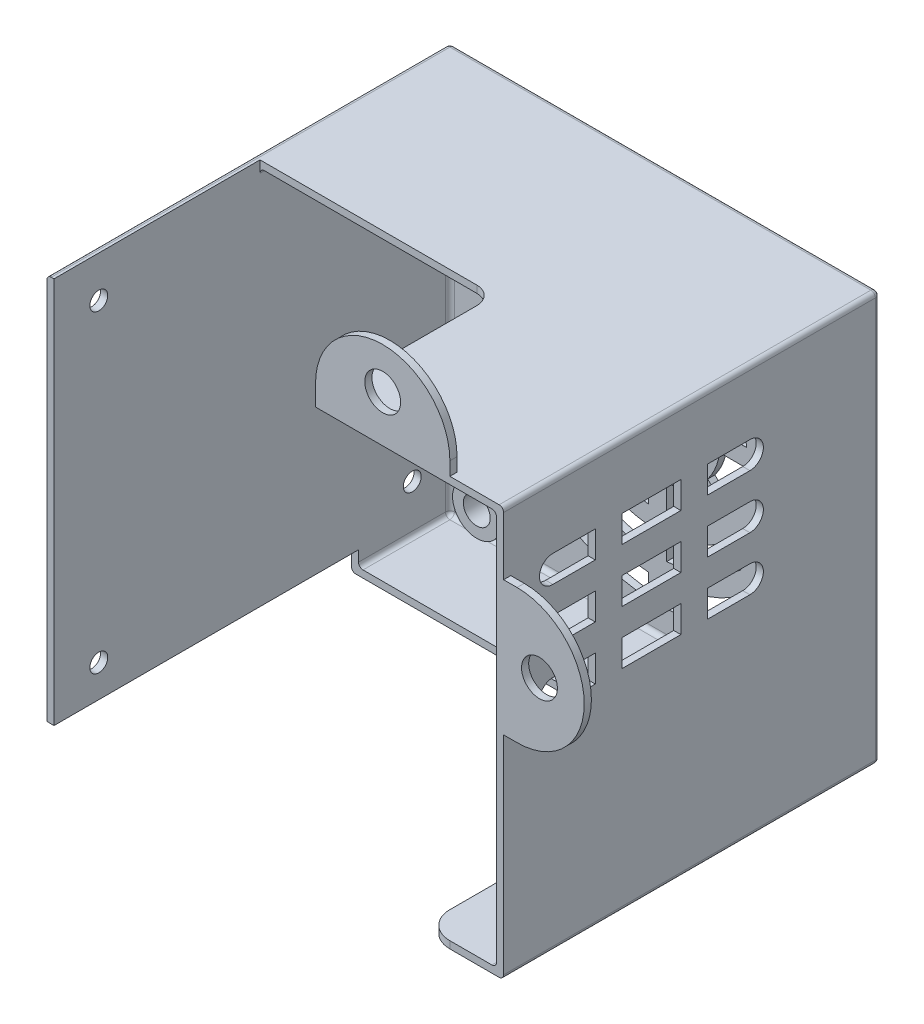
SolidWorks part; units mm, degrees
ref_plane "Front Plane" through (0, 0, 0) normal (0, 0, 1) x (1, 0, 0)
ref_plane "Top Plane" through (0, 0, 0) normal (0, 1, 0) x (1, 0, 0)
ref_plane "Right Plane" through (0, 0, 0) normal (1, 0, 0) x (0, 0, -1)
ref_plane "Plane1" through (0, 0, 42) normal (0, 0, 1) x (1, 0, 0)
sketch "Sketch1" plane through (0, 0, 42) normal (0, 0, 1) x (1, 0, 0)
  line L0 (22.5, 23.6) -> (-25.5, 23.6)
  line L1 (-25.5, 23.6) -> (-25.5, -22.1)
  line L2 (-25.5, -22.1) -> (22.5, -22.1)
  line L3 (22.5, -22.1) -> (22.5, 23.6)
extrude "Boss-Extrude1" add sketch "Sketch1" against normal blind 42
sketch "Sketch2" plane through (0, 23.6, 0) normal (0, 1, 0) x (-1, 0, 0)
  line L0 (25.5, 42) -> (-1.5, 42)
  line L1 (-1.5, 42) -> (-1.5, 22)
  line L2 (-1.5, 22) -> (25.5, 22)
  line L3 (25.5, 22) -> (25.5, 42)
extrude "Cut-Extrude1" cut sketch "Sketch2" against normal through all
sketch "Sketch3" plane through (0, 0, 22) normal (0, 0, 1) x (1, 0, 0)
  line L0 (-25.5, 23.6) -> (-24.7, 23.6)
  line L1 (-24.7, 23.6) -> (-24.7, -19.6)
  line L2 (-24.7, -19.6) -> (-25.5, -19.6)
  line L3 (-25.5, -19.6) -> (-25.5, 23.6)
extrude "Boss-Extrude2" add sketch "Sketch3" along normal blind 23
sketch "Sketch4" plane through (0, 0, 22) normal (0, 0, 1) x (1, 0, 0)
  line L0 (1.5, -22.1) -> (1.5, -19.6)
  line L1 (1.5, -19.6) -> (-25.5, -19.6)
  line L2 (-25.5, -19.6) -> (-25.5, -22.1)
  line L3 (-25.5, -22.1) -> (1.5, -22.1)
extrude "Cut-Extrude2" cut sketch "Sketch4" against normal blind 11
ref_plane "Plane2" through (0, -19.6, 0) normal (0, -1, 0) x (1, 0, 0)
ref_plane "Plane3" through (0, 22.8, 0) normal (0, 1, 0) x (1, 0, 0)
sketch "Sketch6" plane through (0, 22.8, 0) normal (0, 1, 0) x (1, 0, 0)
  line L0 (1.5, -22) -> (1.5, -11)
  line L1 (1.5, -11) -> (-24.7, -11)
  line L2 (-24.7, -11) -> (-24.7, -22)
  line L3 (-24.7, -22) -> (1.5, -22)
extrude "Cut-Extrude3" cut sketch "Sketch6" against normal up to surface up to plane "Plane2"
sketch "Sketch7" plane through (1.5, 0, 0) normal (-1, 0, 0) x (0, 0, 1)
  line L0 (42, 22.8) -> (11, 22.8)
  line L1 (11, 22.8) -> (11, -22.1)
  line L2 (11, -22.1) -> (42, -22.1)
  line L3 (42, -22.1) -> (42, 22.8)
extrude "Cut-Extrude4" cut sketch "Sketch7" against normal blind 12
sketch "Sketch8" plane through (0, 0, 11) normal (0, 0, 1) x (1, 0, 0)
  line L0 (-24.7, -21.3) -> (13.5, -21.3)
  line L1 (13.5, -21.3) -> (13.5, 22.8)
  line L2 (13.5, 22.8) -> (-24.7, 22.8)
  line L3 (-24.7, 22.8) -> (-24.7, -21.3)
extrude "Cut-Extrude5" cut sketch "Sketch8" against normal blind 10.2
ref_plane "Plane4" through (21.7, 0, 0) normal (1, 0, 0) x (0, 0, -1)
sketch "Sketch9" plane through (21.7, 0, 0) normal (1, 0, 0) x (0, 0, -1)
  line L0 (-0.8, -21.3) -> (-0.8, 22.8)
  line L1 (-0.8, 22.8) -> (-42, 22.8)
  line L2 (-42, 22.8) -> (-42, -21.3)
  line L3 (-42, -21.3) -> (-0.8, -21.3)
extrude "Cut-Extrude6" cut sketch "Sketch9" against normal up to next
sketch "Sketch10" plane through (0, 0, 0.8) normal (0, 0, 1) x (1, 0, 0)
  line L0 (-0.5, -6.1782) -> (-0.5, -9.1999)
  line L1 (8.4499, -0.25) -> (5.4282, -0.25)
  arc A0 (5.4282, -0.25) -> (-0.5, -6.1782) centre (-1.5, 0.75) cw
  arc A1 (-0.5, -9.1999) -> (8.4499, -0.25) centre (-1.5, 0.75) ccw
sketch "Sketch11" plane through (0, 0, 0.8) normal (0, 0, 1) x (1, 0, 0)
  line L0 (-0.5, -11.2083) -> (-0.5, -17.2222)
  line L1 (16.4722, -0.25) -> (10.4583, -0.25)
  arc A0 (10.4583, -0.25) -> (-0.5, -11.2083) centre (-1.5, 0.75) cw
  arc A1 (-0.5, -17.2222) -> (16.4722, -0.25) centre (-1.5, 0.75) ccw
sketch "Sketch12" plane through (0, 0, 0.8) normal (0, 0, 1) x (1, 0, 0)
  line L0 (-8.4282, -0.25) -> (-11.4499, -0.25)
  line L1 (-2.5, -9.1999) -> (-2.5, -6.1782)
  arc A0 (-2.5, -6.1782) -> (-8.4282, -0.25) centre (-1.5, 0.75) cw
  arc A1 (-11.4499, -0.25) -> (-2.5, -9.1999) centre (-1.5, 0.75) ccw
sketch "Sketch13" plane through (0, 0, 0.8) normal (0, 0, 1) x (1, 0, 0)
  line L0 (-13.4583, -0.25) -> (-19.4722, -0.25)
  line L1 (-2.5, -17.2222) -> (-2.5, -11.2083)
  arc A0 (-2.5, -11.2083) -> (-13.4583, -0.25) centre (-1.5, 0.75) cw
  arc A1 (-19.4722, -0.25) -> (-2.5, -17.2222) centre (-1.5, 0.75) ccw
sketch "Sketch14" plane through (0, 0, 0.8) normal (0, 0, 1) x (1, 0, 0)
  line L0 (-2.5, 7.6782) -> (-2.5, 10.6999)
  line L1 (-11.4499, 1.75) -> (-8.4282, 1.75)
  arc A0 (-8.4282, 1.75) -> (-2.5, 7.6782) centre (-1.5, 0.75) cw
  arc A1 (-2.5, 10.6999) -> (-11.4499, 1.75) centre (-1.5, 0.75) ccw
sketch "Outer Rings" plane through (0, 0, 0.8) normal (0, 0, 1) x (1, 0, 0)
  line L0 (-2.5, 12.7083) -> (-2.5, 15.2483)
  line L1 (-20.5703, 1.75) -> (-18.0303, 1.75)
  line L2 (-15.9983, 1.75) -> (-13.4583, 1.75)
  line L3 (-2.5, 17.2803) -> (-2.5, 19.8203)
  line L4 (-13.8996, 15.2732) -> (-12.1834, 13.3972)
  line L5 (-16.0232, 13.1496) -> (-14.1472, 11.4334)
  line L6 (-12.6498, 10.0635) -> (-10.7823, 8.3552)
  line L7 (-10.8135, 11.8998) -> (-9.1052, 10.0323)
  line L8 (-9.304, 7.0028) -> (-7.0837, 4.9716)
  line L9 (-7.7528, 8.554) -> (-5.7216, 6.3337)
  line L10 (-11.4499, 1.75) -> (-8.4282, 1.75)
  line L11 (-2.5, 10.6999) -> (-2.5, 7.6782)
  arc A0 (-13.4583, 1.75) -> (-10.7823, 8.3552) centre (-1.5, 0.75) cw
  arc A1 (-2.5, 19.8203) -> (-13.8996, 15.2732) centre (-1.5, 0.75) ccw
  arc A2 (-2.5, 17.2803) -> (-12.1834, 13.3972) centre (-1.4859, 0.7359) ccw
  arc A3 (-2.5, 15.2483) -> (-10.8135, 11.8998) centre (-1.4859, 0.7359) ccw
  arc A4 (-16.0232, 13.1496) -> (-20.5703, 1.75) centre (-1.5, 0.75) ccw
  arc A5 (-14.1472, 11.4334) -> (-18.0303, 1.75) centre (-1.4859, 0.7359) ccw
  arc A6 (-12.6498, 10.0635) -> (-15.9983, 1.75) centre (-1.4859, 0.7359) ccw
  arc A7 (-9.1052, 10.0323) -> (-2.5, 12.7083) centre (-1.5, 0.75) cw
  arc A8 (-2.5, 10.6999) -> (-11.4499, 1.75) centre (-1.5, 0.75) ccw construction
  arc A9 (-2.5, 7.6782) -> (-8.4282, 1.75) centre (-1.5, 0.75) ccw construction
  arc A10 (-11.4499, 1.75) -> (-9.304, 7.0028) centre (-1.5, 0.75) cw
  arc A11 (-8.4282, 1.75) -> (-7.0837, 4.9716) centre (-1.5, 0.75) cw
  arc A12 (-7.7528, 8.554) -> (-2.5, 10.6999) centre (-1.5, 0.75) cw
  arc A13 (-5.7216, 6.3337) -> (-2.5, 7.6782) centre (-1.5, 0.75) cw
  point P5 (-15.0032, 14.2532)
  dimension "D1" = 7.112
  dimension "D2" = 2.54
  dimension "D3" = 2.54
sketch "Sketch16" plane through (0, 0, 0.8) normal (0, 0, 1) x (1, 0, 0)
  line L0 (5.4282, 1.75) -> (8.4499, 1.75)
  line L1 (-0.5, 10.6999) -> (-0.5, 7.6782)
  arc A0 (-0.5, 7.6782) -> (5.4282, 1.75) centre (-1.5, 0.75) cw
  arc A1 (8.4499, 1.75) -> (-0.5, 10.6999) centre (-1.5, 0.75) ccw
sketch "Sketch17" plane through (22.5, 0, 0) normal (1, 0, 0) x (0, 0, -1)
  line L0 (-36.5, 1.4) -> (-14.5, 1.4)
  line L1 (-14.5, 4.4) -> (-36.5, 4.4)
  arc A0 (-36.5, 4.4) -> (-36.5, 1.4) centre (-36.5, 2.9) ccw
  arc A1 (-14.5, 1.4) -> (-14.5, 4.4) centre (-14.5, 2.9) ccw
sketch "Sketch18" plane through (22.5, 0, 0) normal (1, 0, 0) x (0, 0, -1)
  line L0 (-36.5, 7.4) -> (-14.5, 7.4)
  line L1 (-14.5, 10.4) -> (-36.5, 10.4)
  arc A0 (-36.5, 10.4) -> (-36.5, 7.4) centre (-36.5, 8.9) ccw
  arc A1 (-14.5, 7.4) -> (-14.5, 10.4) centre (-14.5, 8.9) ccw
sketch "Sketch19" plane through (22.5, 0, 0) normal (1, 0, 0) x (0, 0, -1)
  line L0 (-36.5, 13.4) -> (-31.7676, 13.4)
  line L1 (-14.5, 16.4) -> (-19.2324, 16.4)
  line L2 (-36.5, 7.4) -> (-31.7676, 7.4)
  line L3 (-14.5, 10.4) -> (-19.2324, 10.4)
  line L4 (-36.5, 1.4) -> (-31.7676, 1.4)
  line L5 (-14.5, 4.4) -> (-19.2324, 4.4)
  line L6 (-36.5, 7.4) -> (-14.5, 7.4) construction
  line L7 (-36.5, 1.4) -> (-14.5, 1.4) construction
  line L8 (-31.7676, 16.4) -> (-31.7676, 13.4)
  line L9 (-28.7924, 16.4) -> (-28.7924, 13.4)
  line L10 (-22.2076, 16.4) -> (-22.2076, 13.4)
  line L11 (-19.2324, 16.4) -> (-19.2324, 13.4)
  line L12 (-31.7676, 10.4) -> (-31.7676, 7.4)
  line L13 (-28.7924, 10.4) -> (-28.7924, 7.4)
  line L14 (-22.2076, 10.4) -> (-22.2076, 7.4)
  line L15 (-19.2324, 10.4) -> (-19.2324, 7.4)
  line L16 (-19.2324, 4.4) -> (-19.2324, 1.4)
  line L17 (-22.2076, 4.4) -> (-22.2076, 1.4)
  line L18 (-28.7924, 4.4) -> (-28.7924, 1.4)
  line L19 (-31.7676, 4.4) -> (-31.7676, 1.4)
  line L20 (-31.7676, 16.4) -> (-36.5, 16.4)
  line L21 (-28.7924, 13.4) -> (-22.2076, 13.4)
  line L22 (-31.7676, 10.4) -> (-36.5, 10.4)
  line L23 (-28.7924, 7.4) -> (-22.2076, 7.4)
  line L24 (-31.7676, 4.4) -> (-36.5, 4.4)
  line L25 (-28.7924, 1.4) -> (-22.2076, 1.4)
  line L26 (-22.2076, 16.4) -> (-28.7924, 16.4)
  line L27 (-19.2324, 13.4) -> (-14.5, 13.4)
  line L28 (-22.2076, 10.4) -> (-28.7924, 10.4)
  line L29 (-19.2324, 7.4) -> (-14.5, 7.4)
  line L30 (-22.2076, 4.4) -> (-28.7924, 4.4)
  line L31 (-19.2324, 1.4) -> (-14.5, 1.4)
  line L32 (-31.7676, 10.4) -> (-28.7924, 10.4) construction
  line L33 (-22.2076, 10.4) -> (-19.2324, 10.4) construction
  arc A0 (-36.5, 16.4) -> (-36.5, 13.4) centre (-36.5, 14.9) ccw
  arc A1 (-14.5, 13.4) -> (-14.5, 16.4) centre (-14.5, 14.9) ccw
  arc A2 (-36.5, 10.4) -> (-36.5, 7.4) centre (-36.5, 8.9) ccw
  arc A3 (-14.5, 7.4) -> (-14.5, 10.4) centre (-14.5, 8.9) ccw
  arc A4 (-36.5, 4.4) -> (-36.5, 1.4) centre (-36.5, 2.9) ccw
  arc A5 (-14.5, 1.4) -> (-14.5, 4.4) centre (-14.5, 2.9) ccw
  arc A6 (-36.5, 10.4) -> (-36.5, 7.4) centre (-36.5, 8.9) ccw construction
  arc A7 (-36.5, 4.4) -> (-36.5, 1.4) centre (-36.5, 2.9) ccw construction
sketch "Sketch21" plane through (0, 0, 42) normal (0, 0, 1) x (1, 0, 0)
  line L0 (1.5, 25.1) -> (1.5, 23.6)
  line L1 (1.5, 23.6) -> (16.5, 23.6)
  line L2 (16.5, 23.6) -> (16.5, 25.1)
  arc A0 (16.5, 25.1) -> (1.5, 25.1) centre (9, 25.1) ccw
extrude "Boss-Extrude3" add sketch "Sketch21" against normal blind 0.8
sketch "Sketch22" plane through (0, 0, 42) normal (0, 0, 1) x (1, 0, 0)
  line L0 (24, 16.6) -> (22.5, 16.6)
  line L1 (22.5, 16.6) -> (22.5, 1.6)
  line L2 (22.5, 1.6) -> (24, 1.6)
  arc A0 (24, 1.6) -> (24, 16.6) centre (24, 9.1) ccw
extrude "Boss-Extrude4" add sketch "Sketch22" against normal blind 0.8
ref_plane "Plane5" through (0, -15.2, 0) normal (0, -1, 0) x (1, 0, 0)
sketch "Sketch23" plane through (0, -15.2, 0) normal (0, -1, 0) x (1, 0, 0)
  line L0 (-14.8, 5) -> (-17.5, 5)
  line L1 (-17.5, 5) -> (-17.5, 0.8)
  line L2 (-17.5, 0.8) -> (-14.8, 0.8)
  line L3 (-14.8, 0.8) -> (-14.8, 5)
  line L4 (-17.5, 5) -> (-17.5, 0.8) construction
revolve "Revolve1" add sketch "Sketch23" angle 360 about L4
ref_plane "Plane6" through (0, 16.8, 0) normal (0, -1, 0) x (1, 0, 0)
sketch "Sketch24" plane through (0, 16.8, 0) normal (0, -1, 0) x (1, 0, 0)
  line L0 (-14.8, 5) -> (-17.5, 5)
  line L1 (-17.5, 5) -> (-17.5, 0.8)
  line L2 (-17.5, 0.8) -> (-14.8, 0.8)
  line L3 (-14.8, 0.8) -> (-14.8, 5)
  line L4 (-17.5, 5) -> (-17.5, 0.8) construction
revolve "Revolve2" add sketch "Sketch24" angle 360 about L4
sketch "Sketch25" plane through (0, -15.2, 0) normal (0, -1, 0) x (1, 0, 0)
  line L0 (17.2, 5) -> (14.5, 5)
  line L1 (14.5, 5) -> (14.5, 0.8)
  line L2 (14.5, 0.8) -> (17.2, 0.8)
  line L3 (17.2, 0.8) -> (17.2, 5)
  line L4 (14.5, 5) -> (14.5, 0.8) construction
revolve "Revolve3" add sketch "Sketch25" angle 360 about L4
sketch "Sketch26" plane through (0, 16.8, 0) normal (0, -1, 0) x (1, 0, 0)
  line L0 (17.2, 5) -> (14.5, 5)
  line L1 (14.5, 5) -> (14.5, 0.8)
  line L2 (14.5, 0.8) -> (17.2, 0.8)
  line L3 (17.2, 0.8) -> (17.2, 5)
  line L4 (14.5, 5) -> (14.5, 0.8) construction
revolve "Revolve4" add sketch "Sketch26" angle 360 about L4
hole_wizard "Ø2.0 (2) Diameter Hole1" positions "Sketch28" profile "Sketch27" hole size "Ø2.0" standard "ANSI Metric"
sketch "Sketch28" plane through (-24.7, 0, 0) normal (1, 0, 0) x (0, 0, -1)
  point P0 (-40, 19)
  point P1 (-40, -16)
  point P2 (-5, -16)
  point P3 (-5, 19)
sketch "Sketch27" plane through (-24.7, 19, 40) normal (0, 1, 0) x (0, 0, -1)
  line L0 (0, 0) -> (0, 0.8)
  line L1 (0, 0.8) -> (1, 0.8)
  line L2 (1, 0.8) -> (1, 0)
  line L5 (1, 0) -> (0, 0)
  line L11 (0, -6.35) -> (0, 107.95) construction
  dimension "Thru Hole Dia." = 2
  dimension "Thru Hole Depth" = 0.8
hole_wizard "Ø4.0 (4) Diameter Hole1" positions "Sketch30" profile "Sketch29" hole size "Ø4.0" standard "ANSI Metric"
sketch "Sketch30" plane through (0, 0, 42) normal (0, 0, 1) x (1, 0, 0)
  point P0 (9, 28)
  point P1 (26.5, 9.1)
sketch "Sketch29" plane through (9, 28, 42) normal (1, 0, 0) x (0, -1, 0)
  line L0 (0, 0) -> (0, 42)
  line L1 (0, 42) -> (2, 42)
  line L2 (2, 42) -> (2, 0)
  line L5 (2, 0) -> (0, 0)
  line L11 (0, -6.35) -> (0, 107.95) construction
  dimension "Thru Hole Dia." = 4
  dimension "Thru Hole Depth" = 42
hole_wizard "Ø3.0 (3) Diameter Hole1" positions "Sketch32" profile "Sketch31" hole size "Ø3.0" standard "ANSI Metric"
sketch "Sketch32" plane through (0, 0, 5) normal (0, 0, 1) x (1, 0, 0)
  point P0 (14.5, 16.8)
  point P1 (14.5, -15.2)
  point P2 (-17.5, 16.8)
  point P3 (-17.5, -15.2)
sketch "Sketch31" plane through (14.5, 16.8, 5) normal (1, 0, 0) x (0, -1, 0)
  line L0 (0, 0) -> (0, 4.2)
  line L1 (0, 4.2) -> (1.5, 4.2)
  line L2 (1.5, 4.2) -> (1.5, 0)
  line L5 (1.5, 0) -> (0, 0)
  line L10 (0, 4.2) -> (-1.5, 4.2) construction
  line L11 (0, -6.35) -> (0, 107.95) construction
  dimension "Hole Dia." = 3
  dimension "Hole Depth" = 4.2
  dimension "Drill Angle" = 180
fillet "Fillet1" radius 0.5 16 edges at (21.7, -21.3, 21.4) (21.7, 22.8, 21.4) (21.7, 0.75, 0.8) (-1.5, -21.3, 0.8) (-24.7, -21.3, 5.9) (-1.5, 22.8, 0.8) (-24.7, 0.75, 0.8) (-24.7, 22.8, 11.4) (22.5, -22.1, 21) (-25.5, 23.6, 22.5) (22.5, 0.75, 0) (-1.5, 23.6, 0) (22.5, 23.6, 21) (-25.5, 0.75, 0) (-1.5, -22.1, 0) (-25.5, -22.1, 5.5)
fillet "Fillet2" radius 2 1 edges at (1.5, 23.2, 22)
fillet "Fillet3" radius 3 2 edges at (13.5, -21.7, 11) (13.5, -21.7, 42)
sketch "Sketch33" plane through (0, 0, 0.8) normal (0, 0, 1) x (1, 0, 0)
sketch "Sketch35" plane through (0, 0, 0) normal (0, 0, -1) x (-1, 0, 0)
  line L2 (20.5703, 1.75) -> (18.0303, 1.75) construction
  point P0 (2.5, 15.2483)
  point P1 (15.9983, 1.75)
  dimension "D1" = 2.54
sketch "Sketch36" plane through (0, 0, 0) normal (0, 0, -1) x (-1, 0, 0)
  line L2 (2.5, 12.7083) -> (2.5, 15.2483) construction
  arc A0 (2.5, 17.2803) -> (18.0303, 1.75) centre (1.5, 0.75) cw
  arc A1 (13.8996, 15.2732) -> (2.5, 19.8203) centre (1.5, 0.75) ccw construction
  dimension "D1" = 2.032
extrude "Cut-Extrude7" cut sketch "Outer Rings" against normal through all contours A2 L3 A1 L1 | L6 A6 L2 A0 | L7 A7 L0 A3 | L10 A11 L8 A10 | L9 A13 L11 A12
pattern_circular "CirPattern1" count 4 every 90 about axis through (-1.5, 0.75, 0) along (0, 0, 1) of "Cut-Extrude7"
extrude "Cut-Extrude8" cut sketch "Sketch19" against normal up to next contours L10 L26 L9 L21 | L27 A1 L1 L11 | L29 A3 L3 L15 | L14 L28 L13 L23 | L22 A2 L2 L12 | L24 A4 L4 L19 | L17 L30 L18 L25 | L31 A5 L5 L16 | L0 L8 L20 A0
